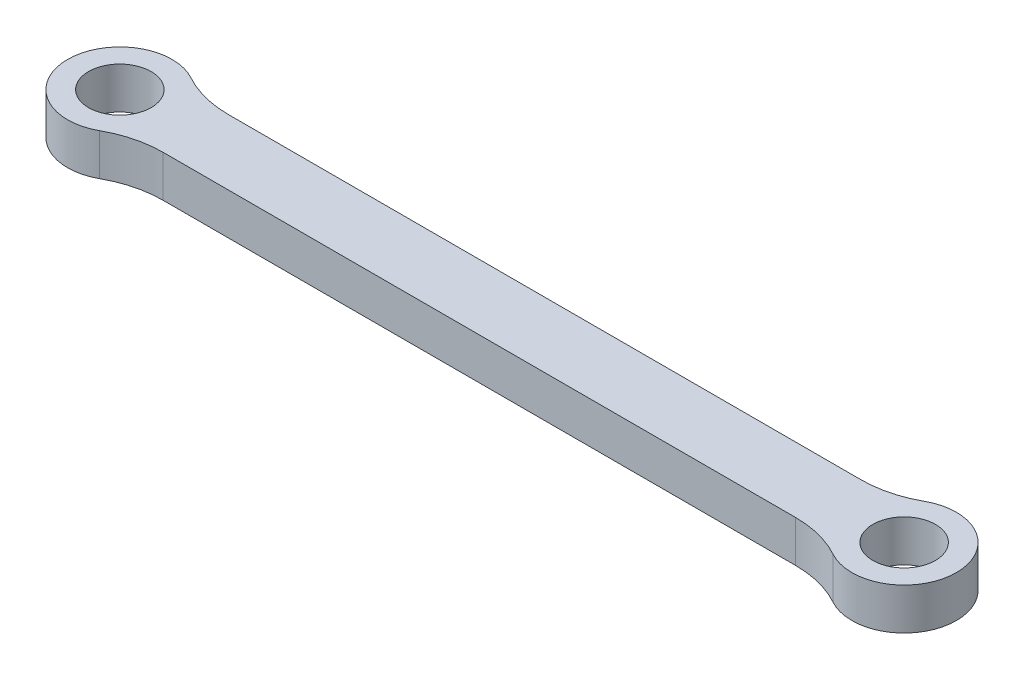
SolidWorks part; units mm, degrees
ref_plane "前视基准面" through (0, 0, 0) normal (0, 0, 1) x (1, 0, 0)
ref_plane "上视基准面" through (0, 0, 0) normal (0, 1, 0) x (1, 0, 0)
ref_plane "右视基准面" through (0, 0, 0) normal (1, 0, 0) x (0, 0, -1)
other "Configuration Table"
sketch "草图1" plane through (0, 0, 0) normal (0, 1, 0) x (1, 0, 0)
  line L1 (-30, 2.5) -> (30, 2.5)
  line L2 (-30, 2.5) -> (-30, -2.5)
  line L3 (-30, -2.5) -> (30, -2.5)
  line L4 (30, 2.5) -> (30, -2.5)
  line L5 (-30, 2.5) -> (30, -2.5) construction
  line L6 (-30, -2.5) -> (30, 2.5) construction
  point P0 (0, 0)
  dimension "D1" = 5
  dimension "D2" = 60
extrude "凸台-拉伸1" add sketch "草图1" along normal blind 3.18
sketch "草图2" plane through (0, 0, 0) normal (0, 1, 0) x (1, 0, 0)
  line L0 (30, -2.5) -> (30, 2.5) construction
  line L1 (-30, 2.5) -> (-30, -2.5) construction
  circle A0 centre (30, 0) radius 4
  circle A1 centre (-30, 0) radius 4
  dimension "D1" = 8
  dimension "D2" = 8
extrude "凸台-拉伸2" add sketch "草图2" along normal up to surface (3.18 mm away) up to face at (0, 3.18, 0)
sketch "草图3" plane through (0, 0, 0) normal (0, 1, 0) x (1, 0, 0)
  line L0 (0, 0) -> (30, 0) construction
  line L1 (30, 0) -> (-30, 0) construction
  circle A0 centre (30, 0) radius 2.395
  circle A1 centre (-30, 0) radius 2.395
  dimension "D3" = 4.79
  dimension "D4" = 4.79
  dimension "D1" = 30
  dimension "D2" = 60
extrude "切除-拉伸1" cut sketch "草图3" along normal up to surface (3.18 mm away) up to face at (0, 3.18, 0)
fillet "圆角3" radius 8 1 edges at (-26.8775, 1.59, -2.5)
fillet "圆角4" radius 8 1 edges at (-26.8775, 1.59, 2.5)
fillet "圆角5" radius 8 2 edges at (26.8775, 1.59, -2.5) (26.8775, 1.59, 2.5)
